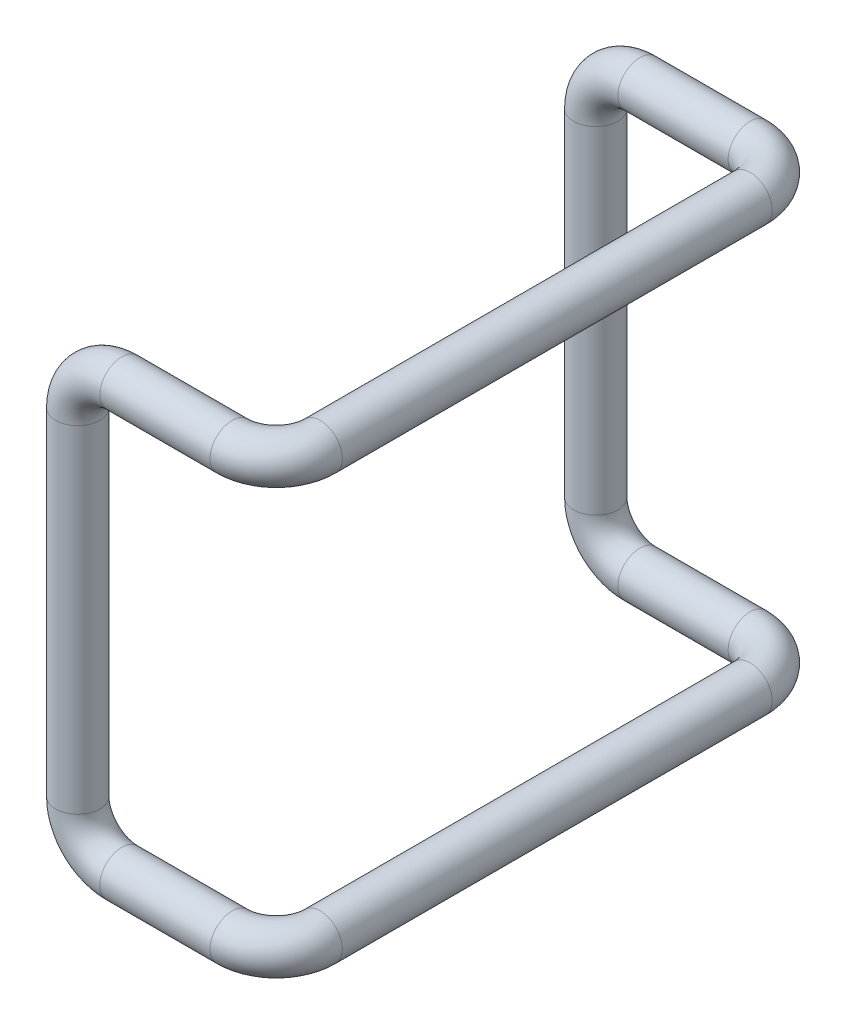
SolidWorks part; units mm, degrees
ref_plane "Front Plane" through (0, 0, 0) normal (0, 0, 1) x (1, 0, 0)
ref_plane "Top Plane" through (0, 0, 0) normal (0, 1, 0) x (1, 0, 0)
ref_plane "Right Plane" through (0, 0, 0) normal (1, 0, 0) x (0, 0, -1)
sketch3d "3DSketch1"
  line L0 (2.54, 12.2314, 14.9174) -> (8.89, 12.2314, 14.9174)
  line L1 (0, 12.2314, -14.9174) -> (0, 12.2314, 14.9174) construction
  line L2 (0, 9.6914, -14.9174) -> (0, -9.6914, -14.9174)
  line L3 (0, -12.2314, -14.9174) -> (0, -12.2314, 14.9174) construction
  line L4 (0, 9.6914, 14.9174) -> (0, -9.6914, 14.9174)
  line L5 (0, 12.2314, -14.9174) -> (0, -12.2314, 14.9174) construction
  line L6 (0, -12.2314, -14.9174) -> (0, 12.2314, 14.9174) construction
  line L7 (2.54, -12.2314, 14.9174) -> (8.89, -12.2314, 14.9174)
  line L8 (2.54, 12.2314, -14.9174) -> (8.89, 12.2314, -14.9174)
  line L9 (2.54, -12.2314, -14.9174) -> (8.89, -12.2314, -14.9174)
  line L10 (11.43, 12.2314, 14.9174) -> (11.43, -12.2314, 14.9174) construction
  line L11 (11.43, -12.2314, 12.3774) -> (11.43, -12.2314, -12.3774)
  line L13 (11.43, 12.2314, -12.3774) -> (11.43, 12.2314, 12.3774)
  arc A0 (0, 9.6914, 14.9174) -> (2.54, 12.2314, 14.9174) centre (2.54, 9.6914, 14.9174) ccw
  arc A1 (8.89, 12.2314, 14.9174) -> (11.43, 12.2314, 12.3774) centre (8.89, 12.2314, 12.3774) ccw
  arc A2 (11.43, 12.2314, -12.3774) -> (8.89, 12.2314, -14.9174) centre (8.89, 12.2314, -12.3774) ccw
  arc A3 (2.54, 12.2314, -14.9174) -> (0, 9.6914, -14.9174) centre (2.54, 9.6914, -14.9174) ccw
  arc A4 (0, -9.6914, -14.9174) -> (2.54, -12.2314, -14.9174) centre (2.54, -9.6914, -14.9174) ccw
  arc A5 (8.89, -12.2314, -14.9174) -> (11.43, -12.2314, -12.3774) centre (8.89, -12.2314, -12.3774) ccw
  arc A6 (11.43, -12.2314, 12.3774) -> (8.89, -12.2314, 14.9174) centre (8.89, -12.2314, 12.3774) ccw
  arc A7 (2.54, -12.2314, 14.9174) -> (0, -9.6914, 14.9174) centre (2.54, -9.6914, 14.9174) ccw
  point P0 (0, 0, 0)
  point P13 (2.54, 9.6914, 12.3774)
  point P17 (8.89, 14.7714, 12.3774)
  point P21 (8.89, 14.7714, -12.3774)
  point P25 (2.54, 9.6914, -12.3774)
  point P29 (2.54, -9.6914, -12.3774)
  point P33 (8.89, -14.7714, -12.3774)
  point P37 (8.89, -14.7714, 12.3774)
  point P41 (2.54, -9.6914, 12.3774)
  dimension "D2" = 2.54
  dimension "D1" = 24.4627
  dimension "D3" = 29.8348
  dimension "D4" = 11.43
sketch "Sketch2" plane through (0, 0, 0) normal (0, 0, 1) x (1, 0, 0)
  circle A0 centre (11.43, 12.2314) radius 1.27
  point P0 (11.43, 12.2314)
  dimension "D1" = 2.54
sweep "Sweep1" add profiles "Sketch2" path "3DSketch1"
